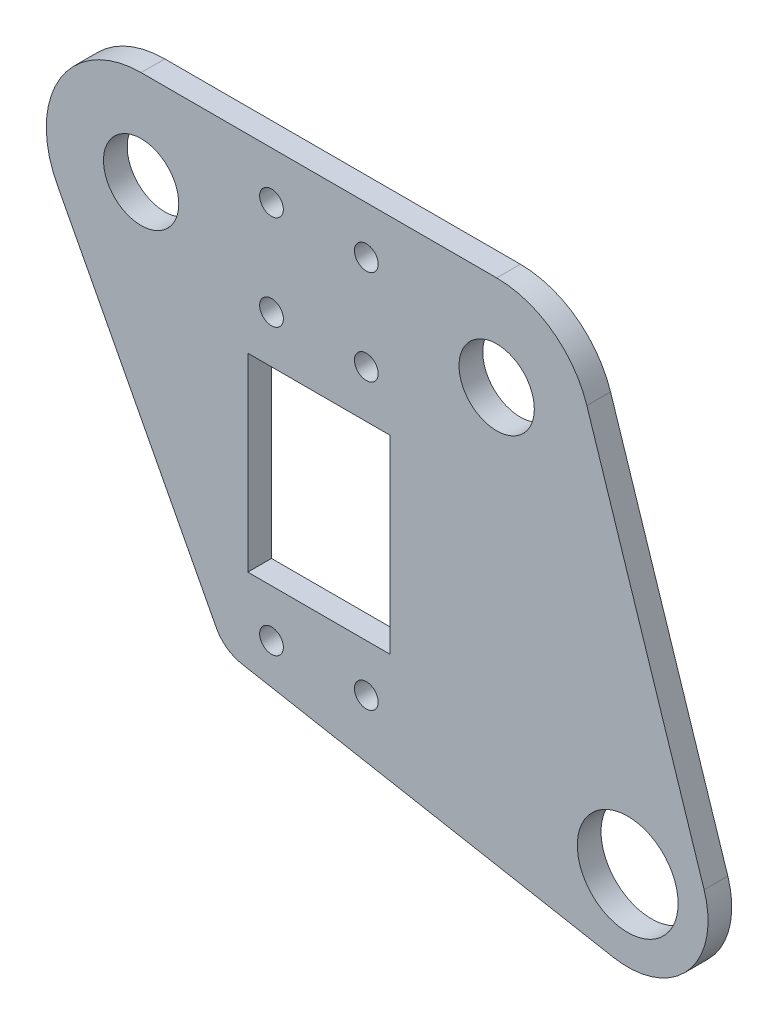
SolidWorks part; units mm, degrees
material "6061 Alloy"
ref_plane "Front" through (0, 0, 0) normal (0, 0, 1) x (1, 0, 0)
ref_plane "Top" through (0, 0, 0) normal (0, 1, 0) x (1, 0, 0)
ref_plane "Right" through (0, 0, 0) normal (1, 0, 0) x (0, 0, -1)
sketch "Sketch1" plane through (0, 0, 0) normal (0, 0, 1) x (1, 0, 0)
  line L0 (-23.8125, 0) -> (23.8125, 0) construction
  line L1 (-23.8125, 12.7) -> (23.8125, 12.7)
  line L2 (0, 0) -> (0, -47.7139) construction
  line L3 (0, -47.7139) -> (41.3639, -47.7139) construction
  line L5 (35.8901, 3.927) -> (51.599, -44.386)
  line L6 (0, 12.7) -> (0, -12.7) construction
  line L7 (-9.525, -12.7) -> (9.525, -12.7)
  line L8 (-9.525, -12.7) -> (-9.525, -38.1)
  line L9 (-9.525, -38.1) -> (9.525, -38.1)
  line L10 (9.525, -12.7) -> (9.525, -38.1)
  line L11 (-35.0666, -5.8852) -> (-13.7453, -46.657)
  line L12 (-10.3869, -49.1339) -> (39.4161, -58.2987)
  line L13 (-9.525, -38.1) -> (-9.525, -44.45) construction
  arc A0 (-23.8125, 12.7) -> (-35.0666, -5.8852) centre (-23.8125, 0) ccw
  arc A1 (23.8125, 12.7) -> (35.8901, 3.927) centre (23.8125, 0) cw
  arc A2 (51.599, -44.386) -> (39.4161, -58.2987) centre (41.3639, -47.7139) cw
  arc A4 (-13.7453, -46.657) -> (-10.3869, -49.1339) centre (-9.525, -44.45) ccw
  dimension "D5" = 10.7625
  dimension "D9" = 6.35
  dimension "D10" = 4.7625
  dimension "D1" = 41.3639
  dimension "D2" = 12.7
  dimension "D3" = 47.7139
  dimension "D4" = 47.625
  dimension "D6" = 25.4
  dimension "D7" = 19.05
  dimension "D8" = 25.4
extrude "Boss-Extrude1" add sketch "Sketch1" along normal blind 3.175
hole_wizard "3/8 Clearance Hole1" positions "Sketch2" profile "Sketch3" hole size "3/8" standard "ANSI Inch" end condition through all
sketch "Sketch2" plane through (0, 0, 3.175) normal (0, 0, 1) x (1, 0, 0)
  point P0 (-23.8125, 0)
  point P3 (23.8125, 0)
sketch "Sketch3" plane through (-23.8125, 0, 3.175) normal (1, 0, 0) x (0, -1, 0)
  line L0 (0, 0) -> (0, 3.175)
  line L1 (0, 3.175) -> (5.0419, 3.175)
  line L2 (5.0419, 3.175) -> (5.0419, 0)
  line L5 (5.0419, 0) -> (0, 0)
  line L11 (0, -6.35) -> (0, 107.95) construction
  dimension "Thru Hole Dia." = 10.0838
  dimension "Thru Hole Depth" = 3.175
hole_wizard "M12 Clearance Hole1" positions "Sketch4" profile "Sketch5" hole size "M12" standard "ANSI Metric" end condition through all
sketch "Sketch4" plane through (0, 0, 3.175) normal (0, 0, 1) x (1, 0, 0)
  point P0 (41.3639, -47.7139)
sketch "Sketch5" plane through (41.3639, -47.7139, 3.175) normal (1, 0, 0) x (0, -1, 0)
  line L0 (0, 0) -> (0, 3.175)
  line L1 (0, 3.175) -> (6.75, 3.175)
  line L2 (6.75, 3.175) -> (6.75, 0)
  line L5 (6.75, 0) -> (0, 0)
  line L11 (0, -6.35) -> (0, 107.95) construction
  dimension "Thru Hole Dia." = 13.5
  dimension "Thru Hole Depth" = 3.175
hole_wizard "1/8 (0.125) Diameter Hole1" positions "Sketch6" profile "Sketch7" hole size "1/8" standard "ANSI Inch" end condition through all
sketch "Sketch6" plane through (0, 0, 3.175) normal (0, 0, 1) x (1, 0, 0)
  line L1 (-6.35, 6.35) -> (6.35, 6.35) construction
  line L2 (-6.35, 6.35) -> (-6.35, -6.35) construction
  line L3 (-6.35, -6.35) -> (6.35, -6.35) construction
  line L4 (6.35, 6.35) -> (6.35, -6.35) construction
  line L5 (-6.35, 6.35) -> (6.35, -6.35) construction
  line L6 (-6.35, -6.35) -> (6.35, 6.35) construction
  line L8 (0, -38.1) -> (0, -44.45) construction
  line L9 (-9.525, -38.1) -> (9.525, -38.1) construction
  line L11 (-6.35, -44.45) -> (6.35, -44.45) construction
  point P1 (6.35, -6.35)
  point P72 (-6.35, 6.35)
  point P73 (-6.35, -6.35)
  point P74 (6.35, 6.35)
  point P97 (-6.35, -44.45)
  point P98 (6.35, -44.45)
  dimension "D1" = 12.7
  dimension "D2" = 12.7
  dimension "D3" = 6.35
sketch "Sketch7" plane through (6.35, -6.35, 3.175) normal (1, 0, 0) x (0, -1, 0)
  line L0 (0, 0) -> (0, 3.175)
  line L1 (0, 3.175) -> (1.5875, 3.175)
  line L2 (1.5875, 3.175) -> (1.5875, 0)
  line L5 (1.5875, 0) -> (0, 0)
  line L11 (0, -6.35) -> (0, 107.95) construction
  dimension "Thru Hole Dia." = 3.175
  dimension "Thru Hole Depth" = 3.175
